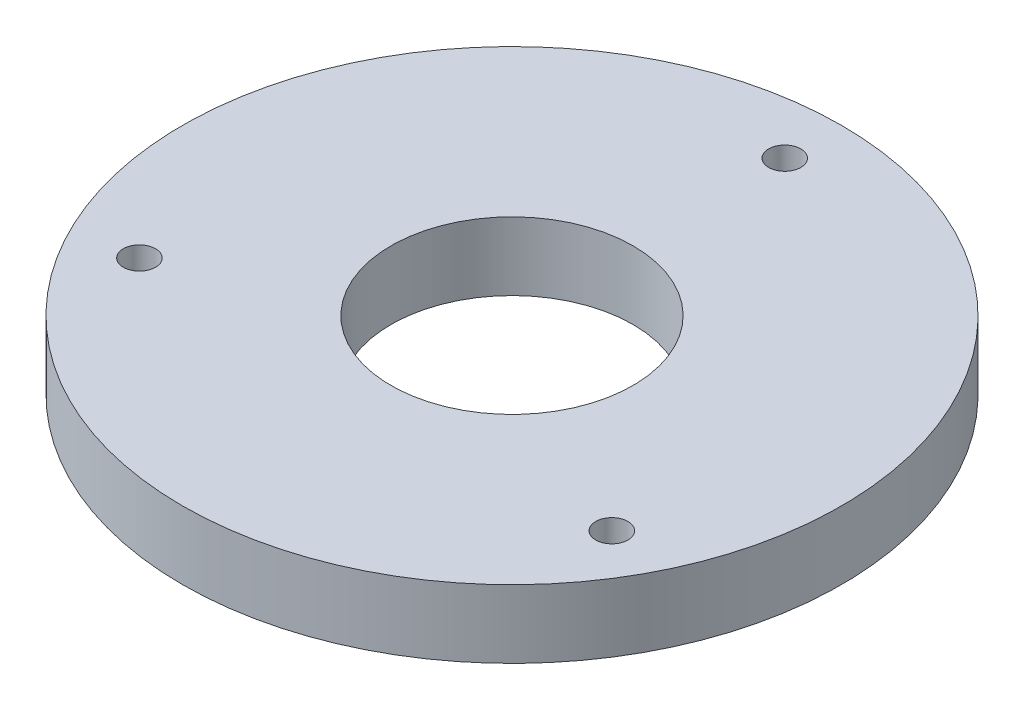
SolidWorks part; units mm, degrees
ref_plane "Front Plane" through (0, 0, 0) normal (0, 0, 1) x (1, 0, 0)
ref_plane "Top Plane" through (0, 0, 0) normal (0, 1, 0) x (1, 0, 0)
ref_plane "Right Plane" through (0, 0, 0) normal (1, 0, 0) x (0, 0, -1)
sketch "Sketch1" plane through (0, 0, 0) normal (0, 1, 0) x (1, 0, 0)
  circle A0 centre (0, 0) radius 36.83
  circle A1 centre (0, 0) radius 13.5255
  dimension "D1" = 73.66
  dimension "D2" = 27.051
extrude "Boss-Extrude1" add sketch "Sketch1" along normal blind 7.62
sketch "Sketch2" plane through (0, 7.62, 0) normal (0, 1, 0) x (1, 0, 0)
  circle A0 centre (0, 30.48) radius 4.7702
  circle A1 centre (26.3965, -15.24) radius 4.7702
  circle A2 centre (-26.3965, -15.24) radius 4.7702
  point P9 (0, 0)
  dimension "D1" = 30.48
  dimension "D2" = 3
hole_wizard "M3 Clearance Hole1" positions "Sketch3" profile "Sketch4" hole size "M3" standard "ANSI Metric" end condition through all
sketch "Sketch3" plane through (0, 7.62, 0) normal (0, 1, 0) x (1, 0, 0)
  point P0 (0, 30.48)
  point P3 (26.3965, -15.24)
  point P6 (-26.3965, -15.24)
sketch "Sketch4" plane through (0, 7.62, -30.48) normal (1, 0, 0) x (0, 0, 1)
  line L0 (0, 0) -> (0, 7.62)
  line L1 (0, 7.62) -> (1.8, 7.62)
  line L2 (1.8, 7.62) -> (1.8, 0)
  line L5 (1.8, 0) -> (0, 0)
  line L11 (0, -6.35) -> (0, 107.95) construction
  dimension "Thru Hole Dia." = 3.6
  dimension "Thru Hole Depth" = 7.62
